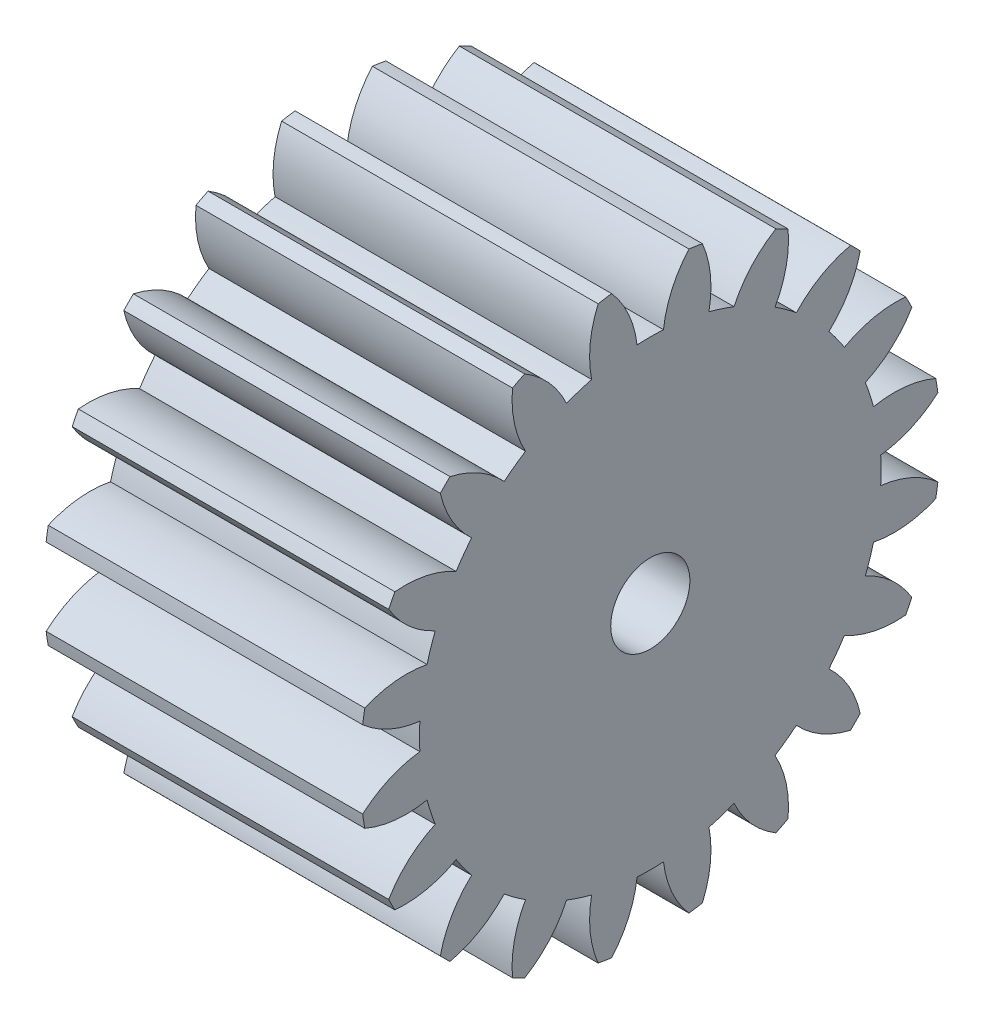
SolidWorks part; units mm, degrees
ref_plane "Plane1" through (0, 0, 0) normal (0, 0, 1) x (1, 0, 0)
ref_plane "Plane2" through (0, 0, 0) normal (0, 1, 0) x (1, 0, 0)
ref_plane "Plane3" through (0, 0, 0) normal (1, 0, 0) x (0, 0, -1)
sketch "HoldingSke" plane through (0, 0, 0) normal (0, 1, 0) x (1, 0, 0)
  line L0 (0, 0) -> (0.9397, -0.342)
  line L1 (-15, 0) -> (100, 0) construction
  line L2 (0, 0) -> (-2.1039, 2.3779)
  line L3 (0, 0) -> (-11.863, 4.5341)
  line L4 (0, 0) -> (8.1152, 2.9537)
  line L5 (0, 0) -> (-46.8476, -17.4728)
  line L6 (0, 0) -> (-9.9476, -6.7116)
  line L7 (-2.1039, 2.3779) -> (8.6586, 51.2059)
  line L8 (-76.2, 54.61) -> (-75.7, 54.61)
  line L9 (-71.009, 38.7566) -> (-53.1078, 45.2721)
  line L10 (-76.2, 71.12) -> (104.1128, 71.12)
  line L11 (0, 0) -> (-12, 0)
  line L12 (-76.2, 101.6) -> (-76.162, 101.6)
  line L13 (24.9733, 27.94) -> (52.9518, 28.4284)
  line L14 (24.9733, 27.94) -> (24.9743, 27.94)
  line L15 (24.9733, 27.94) -> (100.4006, 29.5858)
  line L16 (-63.627, -1) -> (-12.827, -1)
  circle A0 centre (0, 0) radius 1.5
  circle A1 centre (0, 0) radius 8.749
  circle A2 centre (0, 0) radius 37.5
  circle A3 centre (0, 0) radius 1.5
  dimension "MHD" = 17.498
  dimension "Hub_dia" = 75
  dimension "Bore" = 3
  dimension "MBD" = 3
  dimension "Num_teeth" = 20
  dimension "Pitch" = 1
  dimension "Overall_len" = 50
  dimension "Show_teeth" = 20
  dimension "Thickness" = 12
  dimension "OAL" = 50.0001
  dimension "T_dim" = 0.5
  dimension "Ap" = 20
  dimension "H" = 19.05
  dimension "Pitch_radius" = 180.3128
  dimension "Width" = 12
  dimension "Backlash" = 0.038
  dimension "Addendum_fac" = 1
  dimension "Dedendum_fac" = 1.25
  dimension "Clearance_fac" = 0.25
  dimension "Dedendum_add" = 0.001
  dimension "Module" = 1
sketch "BasProSke" plane through (0, 0, 0) normal (0, 1, 0) x (1, 0, 0)
  line L0 (-10, 0) -> (60, 0) construction
  line L1 (0, 0) -> (0, 11)
  line L2 (0, 0) -> (12, 0)
  line L3 (12, 0) -> (12, 11)
  line L4 (12, 11) -> (0, 11)
  dimension "Thickness" = 12
  dimension "Diameter" = 22
revolve "Base-Revolve" add sketch "BasProSke" angle 360 about L0
sketch "TooCutSke" plane through (0, 0, 0) normal (1, 0, 0) x (0, 0, -1)
  line L1 (0, 0) -> (0, 107) construction
  line L2 (0, 0) -> (-0.8511, 9.9637) construction
  line L3 (0, 0) -> (-3.1206, 19.7028) construction
  line L4 (-0.8511, 9.9637) -> (-1.5603, 9.8514) construction
  arc A0 (0.4999, 8.7347) -> (-0.4999, 8.7347) centre (0, 0) ccw
  arc A1 (1.4852, 10.9249) -> (-1.4852, 10.9249) centre (0, 0) ccw
  circle A2 centre (0, 0) radius 10 construction
  circle A3 centre (0, 0) radius 9.3969 construction
  arc A4 (-0.4999, 8.7347) -> (-1.4852, 10.9249) centre (-4.4722, 8.2645) ccw
  arc A5 (1.4852, 10.9249) -> (0.4999, 8.7347) centre (4.4722, 8.2645) ccw
  dimension "Root_dia" = 17.498
  dimension "Overcut_dia" = 22.0508
  dimension "Pitch_dia" = 20
  dimension "Base_dia" = 18.7939
  dimension "Flank_rad" = 4
  dimension "Half_ang" = 9
  dimension "Half_CT" = 0.7181
extrude "ToothCut" cut sketch "TooCutSke" along normal through all
fillet "Breaks" [suppressed] radius 0.02
fillet "RootFillets" [suppressed] radius 0.251
pattern_circular "TeethCuts" count 20 every 18 about axis through (-10, 0, 0) along (1, 0, 0) of "ToothCut", "RootFillets", "Breaks"
sketch "HubNeaOneSke" plane through (0, 0, 0) normal (-1, 0, 0) x (0, 0, 1)
  circle A0 centre (0, 0) radius 8.749
  dimension "Diameter" = 17.498
extrude "HubNearOne" [suppressed] add sketch "HubNeaOneSke" along normal blind 38.0001
sketch "HubNeaBotSke" plane through (0, 0, 0) normal (-1, 0, 0) x (0, 0, 1)
  circle A0 centre (0, 0) radius 8.749
  dimension "Diameter" = 17.498
extrude "HubNearBoth" [suppressed] add sketch "HubNeaBotSke" along normal blind 19
ref_plane "FarPln" through (12, 0, 0) normal (1, 0, 0) x (0, 0, -1)
sketch "HubFarSke" plane through (12, 0, 0) normal (1, 0, 0) x (0, 0, -1)
  circle A0 centre (0, 0) radius 8.749
  dimension "Diameter" = 17.498
extrude "HubFar" [suppressed] add sketch "HubFarSke" along normal blind 19
sketch "BorSke" plane through (0, 0, 0) normal (1, 0, 0) x (0, 0, -1)
  circle A0 centre (0, 0) radius 1.5
  dimension "Diameter" = 3
extrude "Bore" cut sketch "BorSke" along normal mid plane 100.0001
sketch "KeySke" plane through (0, 0, 0) normal (1, 0, 0) x (0, 0, -1)
  line L0 (-0.6, 0) -> (-0.6, 2)
  line L1 (-0.6, 2) -> (0.6, 2)
  line L2 (0.6, 2) -> (0.6, 0)
  line L3 (0, 0) -> (0, 34) construction
  line L4 (-0.6, 0) -> (0.6, 0)
  dimension "Offset" = 2
extrude "Keyway" [suppressed] cut sketch "KeySke" along normal mid plane 100.0001
pattern_circular "Keyway2" [suppressed] count 2 every 90 about axis through (-10, 0, 0) along (1, 0, 0)
sketch "Sketch1" plane through (12, 0, 0) normal (1, 0, 0) x (0, 0, -1)
  circle A0 centre (0, 0) radius 10 construction
  dimension "D1" = 20
equation "' \"Module@HoldingSke\" = 6.35"
equation "' \"Num_teeth@HoldingSke\" = 12"
equation "' \"Ap@HoldingSke\" =  20"
equation "' \"Ap@HoldingSke\" = 20"
equation "' \"Width@HoldingSke\" = 0.5 * 25.4"
equation "' \"Hub_dia@HoldingSke\"= 1 * 25.4"
equation "' \"Hub_dia@HoldingSke\" = 1 * 25.4"
equation "' \"Overall_len@HoldingSke\" = 1.0 * 25.4"
equation "' \"Bore@HoldingSke\" = 0.75 * 25.4"
equation "' \"T_dim@HoldingSke\" = 0.1 * 25.4"
equation "' \"Width@KeySke\" = 0.25 * 25.4"
equation "' \"Show_teeth@HoldingSke\" = 13"
equation "' \"Backlash@HoldingSke\" = 0.009 * 25.4"
equation "' \"Addendum_fac@HoldingSke\" = 1.0"
equation "' \"Dedendum_fac@HoldingSke\" = 1.25"
equation "' \"Dedendum_add@HoldingSke\" = 0.00005 * 25.4"
equation "' \"Clearance_fac@HoldingSke\" = 0.25"
equation "\"Pitch@HoldingSke\" = 1 / \"Module@HoldingSke\""
equation "\"Overcut_dia@TooCutSke\" = (\"Num_teeth@HoldingSke\" + 2 * \"Addendum_fac@HoldingSke\") / \"Pitch@HoldingSke\" + 0.002 * 25.4"
equation "\"Pitch_dia@TooCutSke\" = \"Num_teeth@HoldingSke\" / \"Pitch@HoldingSke\""
equation "\"Base_dia@TooCutSke\" = \"Num_teeth@HoldingSke\" / \"Pitch@HoldingSke\" * cos((\"Ap@HoldingSke\"  * 3.14159265 / 180))"
equation "\"Root_dia@TooCutSke\" = (\"Num_teeth@HoldingSke\" + 2) / \"Pitch@HoldingSke\" - 2 * (\"Addendum_fac@HoldingSke\" + \"Dedendum_fac@HoldingSke\") / \"Pitch@HoldingSke\" - \"Dedendum_add@HoldingSke\" * 2"
equation "\"Half_ang@TooCutSke\" = 180 / \"Num_teeth@HoldingSke\""
equation "\"Half_CT@TooCutSke\" = \"Num_teeth@HoldingSke\" / \"Pitch@HoldingSke\" * sin((3.14159265 / 2 / \"Num_teeth@HoldingSke\")) / 2 - 7 * \"Backlash@HoldingSke\" / 4"
equation "\"Flank_rad@TooCutSke\" = \"Num_teeth@HoldingSke\" / \"Pitch@HoldingSke\" / 5"
equation "\"Radius@RootFillets\" = \"Clearance_fac@HoldingSke\" / \"Pitch@HoldingSke\" + \"Dedendum_add@HoldingSke\""
equation "\"Break_rad@Breaks\" = 0.02 / \"Pitch@HoldingSke\""
equation "\"Thickness@HoldingSke\" = \"Width@HoldingSke\""
equation "\"OAL@HoldingSke\" = \"Thickness@HoldingSke\""
equation "\"MHD@HoldingSke\" = (\"Num_teeth@HoldingSke\" + 2) / \"Pitch@HoldingSke\" - 2 * (\"Addendum_fac@HoldingSke\" + \"Dedendum_fac@HoldingSke\")  / \"Pitch@HoldingSke\" - \"Dedendum_add@HoldingSke\" * 2"
equation "\"MBD@HoldingSke\" = (\"Num_teeth@HoldingSke\" + 2) / \"Pitch@HoldingSke\" - 2 * (\"Addendum_fac@HoldingSke\" + \"Dedendum_fac@HoldingSke\")  / \"Pitch@HoldingSke\" - \"Dedendum_add@HoldingSke\" * 2 - 0.002 * 25.4"
equation "\"MHD@HoldingSke\" = ((sgn( \"MHD@HoldingSke\" - \"Hub_dia@HoldingSke\" )-1)*( \"MHD@HoldingSke\" - \"Hub_dia@HoldingSke\" ))/-2+ \"Hub_dia@HoldingSke\""
equation "\"MBD@HoldingSke\" = ((sgn( \"MBD@HoldingSke\" - \"Bore@HoldingSke\" )-1)*( \"MBD@HoldingSke\" - \"Bore@HoldingSke\" ))/-2+ \"Bore@HoldingSke\""
equation "\"OAL@HoldingSke\" = ((sgn( \"OAL@HoldingSke\" - \"Overall_len@HoldingSke\" )+1)*( \"OAL@HoldingSke\" - \"Overall_len@HoldingSke\" ))/2 + \"Overall_len@HoldingSke\" + 0.000002 * 25.4"
equation "\"Num_teeth@TeethCuts\" = int( \"Show_teeth@HoldingSke\" ) + 1"
equation "\"Num_teeth@TeethCuts\" = ((sgn( \"Num_teeth@TeethCuts\" - \"Num_teeth@HoldingSke\" )-1)*( \"Num_teeth@TeethCuts\" - \"Num_teeth@HoldingSke\" ))/-2+ \"Num_teeth@HoldingSke\""
equation "\"Num_teeth@TeethCuts\" = ((sgn( \"Num_teeth@TeethCuts\" - 2.0)+1)*( \"Num_teeth@TeethCuts\" - 2.0))/2 +2.0"
equation "\"Angle@TeethCuts\" = 360.0 / \"Num_teeth@HoldingSke\""
equation "\"Diameter@BasProSke\" = (\"Num_teeth@HoldingSke\" + 2 * \"Addendum_fac@HoldingSke\") / \"Pitch@HoldingSke\""
equation "\"Thickness@BasProSke\"  = \"Thickness@HoldingSke\""
equation "' \"Fillet_rad@BasProSke\" =  \"Thickness@HoldingSke\" * 0.05"
equation "' \"Fillet_rad@BasProSke\" = \"Thickness@HoldingSke\" * 0.05"
equation "\"MHD@HoldingSke\" = ((sgn( \"MHD@HoldingSke\" - \"Root_dia@TooCutSke\" )-1)*( \"MHD@HoldingSke\" - \"Root_dia@TooCutSke\" ))/-2+ \"Root_dia@TooCutSke\""
equation "\"Diameter@HubNeaOneSke\" = \"MHD@HoldingSke\""
equation "\"Length@HubNearOne\" = \"OAL@HoldingSke\" - \"Thickness@BasProSke\""
equation "\"Diameter@HubNeaBotSke\" = \"MHD@HoldingSke\""
equation "\"Length@HubNearBoth\" = ( \"OAL@HoldingSke\" - \"Thickness@BasProSke\" ) / 2.0"
equation "\"Thickness@FarPln\" = \"Thickness@BasProSke\""
equation "\"Diameter@HubFarSke\" = \"MHD@HoldingSke\""
equation "\"Length@HubFar\" = ( \"OAL@HoldingSke\" - \"Thickness@BasProSke\" ) / 2.0"
equation "\"Diameter@BorSke\" = \"MBD@HoldingSke\""
equation "\"D1@Bore\" = \"OAL@HoldingSke\" * 2.0"
equation "\"D1@Keyway\" = \"OAL@HoldingSke\" * 2.0"
equation "\"Offset@KeySke\" = \"T_dim@HoldingSke\" + \"MBD@HoldingSke\" / 2.0"
